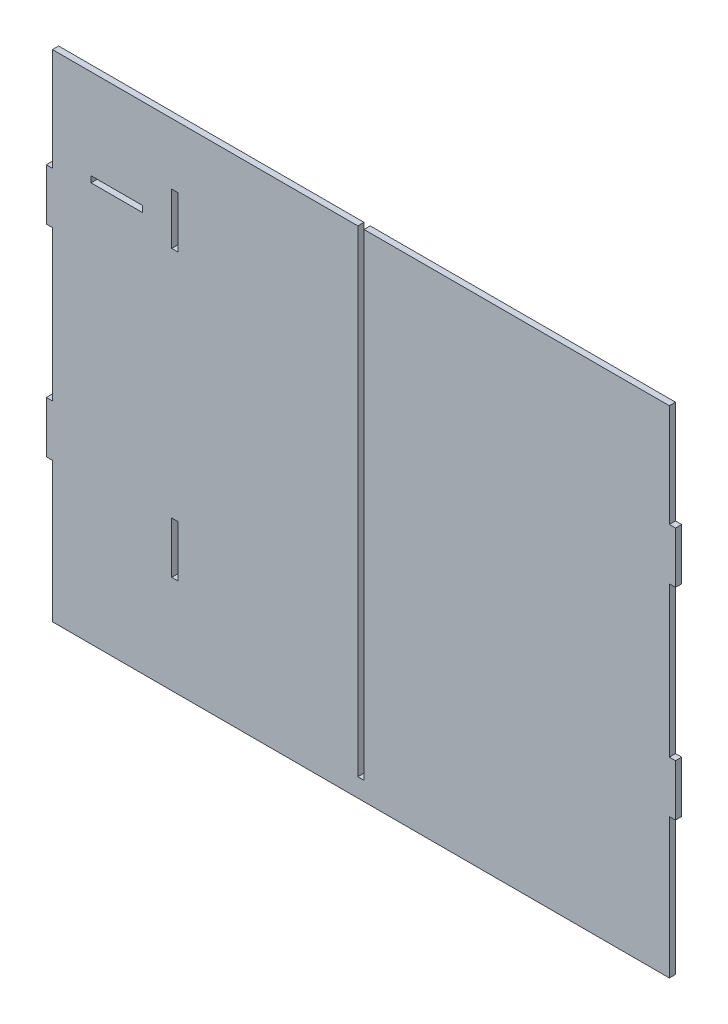
SolidWorks part; units mm, degrees
material "Maple"
ref_plane "Front Plane" through (0, 0, 0) normal (0, 0, 1) x (1, 0, 0)
ref_plane "Top Plane" through (0, 0, 0) normal (0, 1, 0) x (1, 0, 0)
ref_plane "Right Plane" through (0, 0, 0) normal (1, 0, 0) x (0, 0, -1)
sketch "Sketch1" plane through (0, 0, 0) normal (0, 0, 1) x (1, 0, 0)
  line L6 (300, -464) -> (300, 0) construction
  line L55 (0, 0) -> (297, 0)
  line L56 (0, 0) -> (0, -100)
  line L57 (0, -482) -> (600, -482)
  line L58 (600, 0) -> (600, -100)
  line L64 (297, 0) -> (297, -464)
  line L65 (297, -464) -> (303, -464)
  line L77 (303, 0) -> (303, -464)
  line L78 (303, 0) -> (600, 0)
  line L79 (300, -223) -> (297, -223) construction
  line L81 (116, -336.5) -> (122, -336.5)
  line L82 (116, -59.5) -> (122, -59.5)
  line L83 (116, -59.5) -> (116, -109.5)
  line L84 (116, -109.5) -> (122, -109.5)
  line L85 (122, -59.5) -> (122, -109.5)
  line L86 (116, -59.5) -> (122, -109.5) construction
  line L87 (116, -109.5) -> (122, -59.5) construction
  line L88 (122, -386.5) -> (122, -336.5)
  line L89 (116, -386.5) -> (122, -386.5)
  line L90 (116, -386.5) -> (116, -336.5)
  line L103 (0, -150) -> (-6, -150)
  line L104 (37.5, -87.5) -> (87.5, -87.5)
  line L105 (37.5, -87.5) -> (37.5, -93.5)
  line L106 (37.5, -93.5) -> (87.5, -93.5)
  line L107 (87.5, -87.5) -> (87.5, -93.5)
  line L108 (37.5, -87.5) -> (87.5, -93.5) construction
  line L109 (37.5, -93.5) -> (87.5, -87.5) construction
  line L110 (600, -100) -> (606, -100)
  line L112 (600, -150) -> (606, -150)
  line L113 (606, -100) -> (606, -150)
  line L114 (600, -346) -> (600, -482)
  line L116 (-6, -100) -> (-6, -150)
  line L117 (0, -100) -> (-6, -100)
  line L119 (600, -296) -> (606, -296)
  line L120 (606, -346) -> (606, -296)
  line L121 (600, -346) -> (606, -346)
  line L124 (0, -346) -> (-6, -346)
  line L125 (-6, -346) -> (-6, -296)
  line L126 (0, -296) -> (-6, -296)
  line L127 (0, -346) -> (0, -482)
  line L128 (0, -150) -> (0, -296)
  line L129 (600, -150) -> (600, -296)
  point P0 (-416.8486, 134.664)
  point P15 (125, -84.5)
  point P25 (75, -241)
  point P34 (62.5, -90.5)
  point P41 (600, -43)
  dimension "D1" = 482
  dimension "D2" = 600
  dimension "D3" = 18
  dimension "D4" = 300
  dimension "D5" = 6
  dimension "D6" = 300
  dimension "D7" = 6
  dimension "D8" = 50
  dimension "D9" = 297
  dimension "D10" = 300
  dimension "D11" = 50
  dimension "D12" = 28.5
  dimension "D13" = 6
  dimension "D14" = 6
  dimension "D15" = 50
  dimension "D16" = 136
  dimension "D17" = 100
  dimension "D18" = 37.5
extrude "Boss-Extrude1" add sketch "Sketch1" along normal blind 6
